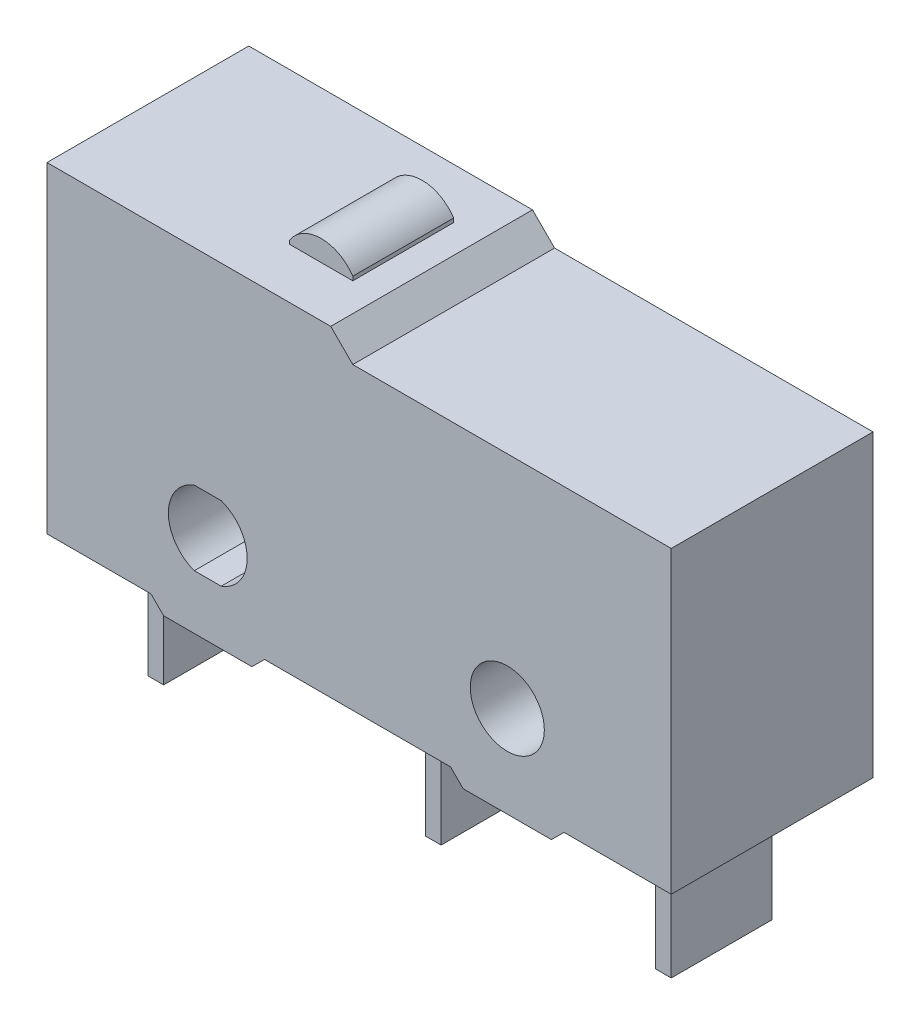
SolidWorks part; units mm, degrees
ref_plane "Front Plane" through (0, 0, 0) normal (0, 0, 1) x (1, 0, 0)
ref_plane "Top Plane" through (0, 0, 0) normal (0, 1, 0) x (1, 0, 0)
ref_plane "Right Plane" through (0, 0, 0) normal (1, 0, 0) x (0, 0, -1)
ref_plane "Plane1" through (0, 0, 3.2) normal (0, 0, 1) x (1, 0, 0)
sketch "Sketch1" plane through (0, 0, 3.2) normal (0, 0, 1) x (1, 0, 0)
  line L0 (-14.6, -2.9) -> (5.2, -2.9)
  line L1 (5.2, -2.9) -> (5.2, 7.7)
  line L2 (5.2, 7.7) -> (-14.6, 7.7)
  line L3 (-14.6, 7.7) -> (-14.6, -2.9)
  point P7 (-38.6715, 20.108)
  dimension "D1" = 19.8
  dimension "D2" = 10.6
  dimension "D3" = 14.6
  dimension "D4" = 7.7
extrude "Boss-Extrude1" add sketch "Sketch1" against normal blind 6.4
sketch "Sketch2" plane through (0, 0, -3.2) normal (0, 0, -1) x (-1, 0, 0)
  line L0 (-5.2, 7) -> (5.6, 7)
  line L1 (5.6, 7) -> (5.6, 7.7)
  line L2 (5.6, 7.7) -> (-5.2, 7.7)
  line L3 (-5.2, 7.7) -> (-5.2, 7)
extrude "Cut-Extrude1" cut sketch "Sketch2" against normal through all
sketch "Sketch3" plane through (0, 0, -3.2) normal (0, 0, -1) x (-1, 0, 0)
  line L0 (14.6, -2.5) -> (11.3, -2.5)
  line L1 (11.3, -2.5) -> (11.3, -2.9)
  line L2 (11.3, -2.9) -> (14.6, -2.9)
  line L3 (14.6, -2.9) -> (14.6, -2.5)
extrude "Cut-Extrude2" cut sketch "Sketch3" against normal through all
sketch "Sketch4" plane through (0, 0, -3.2) normal (0, 0, -1) x (-1, 0, 0)
  line L0 (1.8, -2.9) -> (7.7, -2.9)
  line L1 (7.7, -2.9) -> (7.7, -2.5)
  line L2 (7.7, -2.5) -> (1.8, -2.5)
  line L3 (1.8, -2.5) -> (1.8, -2.9)
extrude "Cut-Extrude3" cut sketch "Sketch4" against normal through all
sketch "Sketch5" plane through (0, 0, -3.2) normal (0, 0, -1) x (-1, 0, 0)
  line L0 (-1.8, -2.5) -> (-5.2, -2.5)
  line L1 (-5.2, -2.5) -> (-5.2, -2.9)
  line L2 (-5.2, -2.9) -> (-1.8, -2.9)
  line L3 (-1.8, -2.9) -> (-1.8, -2.5)
extrude "Cut-Extrude4" cut sketch "Sketch5" against normal through all
sketch "Sketch6" plane through (0, 0, -3.2) normal (0, 0, -1) x (-1, 0, 0)
  line L0 (9.0735, -1.175) -> (9.9265, -1.175)
  line L1 (9.9265, 1.175) -> (9.0735, 1.175)
  arc A0 (9.0735, 1.175) -> (9.0735, -1.175) centre (9.5, 0) ccw
  arc A1 (9.9265, -1.175) -> (9.9265, 1.175) centre (9.5, 0) ccw
extrude "Cut-Extrude5" cut sketch "Sketch6" against normal through all
ref_plane "Plane2" through (0, 0, 1.6) normal (0, 0, 1) x (1, 0, 0)
sketch "Sketch7" plane through (0, 0, 1.6) normal (0, 0, 1) x (1, 0, 0)
  line L0 (-8.5, 7.8256) -> (-8.5, 7.7)
  line L1 (-8.5, 7.7) -> (-6.5, 7.7)
  line L2 (-6.5, 7.7) -> (-6.5, 7.8256)
  arc A0 (-6.5, 7.8256) -> (-8.5, 7.8256) centre (-7.5, 7.1623) ccw
extrude "Boss-Extrude2" add sketch "Sketch7" against normal blind 3.2
sketch "Sketch8" plane through (0, -2.5, 0) normal (0, -1, 0) x (1, 0, 0)
  line L0 (-4.2, 1.6) -> (-3.7, 1.6)
  line L1 (-3.7, 1.6) -> (-3.7, -1.6)
  line L2 (-3.7, -1.6) -> (-4.2, -1.6)
  line L3 (-4.2, -1.6) -> (-4.2, 1.6)
extrude "Boss-Extrude3" add sketch "Sketch8" along normal blind 3.9
sketch "Sketch9" plane through (0, -2.5, 0) normal (0, -1, 0) x (1, 0, 0)
  line L0 (3.1, 1.6) -> (3.6, 1.6)
  line L1 (3.6, 1.6) -> (3.6, -1.6)
  line L2 (3.6, -1.6) -> (3.1, -1.6)
  line L3 (3.1, -1.6) -> (3.1, 1.6)
extrude "Boss-Extrude4" add sketch "Sketch9" along normal blind 3.9
sketch "Sketch10" plane through (0, -2.5, 0) normal (0, -1, 0) x (1, 0, 0)
  line L0 (-12.5, 1.6) -> (-12.5, -1.6)
  line L1 (-12.5, -1.6) -> (-13, -1.6)
  line L2 (-13, -1.6) -> (-13, 1.6)
  line L3 (-13, 1.6) -> (-12.5, 1.6)
extrude "Boss-Extrude5" add sketch "Sketch10" along normal blind 3.9
draft "Draft1" type of draft neutral plane draft angle 45 faces to draft 1 face at (-5.6, 7.35, 0) neutral plane through (5.2, 7.7, -3.2) neutral plane normal (0, 1, 0) parameters "D1"=45
draft "Draft2" type of draft neutral plane draft angle 45 faces to draft 1 face at (1.8, -2.7, 0) neutral plane through (1.8, -2.5, 3.2) neutral plane normal (0, -1, 0) parameters "D1"=45
draft "Draft3" type of draft neutral plane draft angle 45 faces to draft 1 face at (-11.3, -2.7, 0) neutral plane through (-14.6, -2.5, 3.2) neutral plane normal (0, -1, 0) parameters "D1"=45
draft "Draft4" type of draft neutral plane draft angle 45 faces to draft 2 face at (-7.7, -2.7, 0) face at (-1.8, -2.7, 0) neutral plane through (-7.7, -2.5, 3.2) neutral plane normal (0, -1, 0) parameters "D1"=45
hole_wizard "Ø2.35 (2.35) Diameter Hole1" positions "Sketch12" profile "Sketch11" hole size "Ø2.35" standard "ANSI Metric"
sketch "Sketch12" plane through (0, 0, 3.2) normal (0, 0, 1) x (1, 0, 0)
  point P0 (0, 0)
sketch "Sketch11" plane through (0, 0, 3.2) normal (1, 0, 0) x (0, -1, 0)
  line L0 (0, 0) -> (0, 6.4)
  line L1 (0, 6.4) -> (1.175, 6.4)
  line L2 (1.175, 6.4) -> (1.175, 0)
  line L5 (1.175, 0) -> (0, 0)
  line L11 (0, -6.35) -> (0, 107.95) construction
  dimension "Thru Hole Dia." = 2.35
  dimension "Thru Hole Depth" = 6.4
